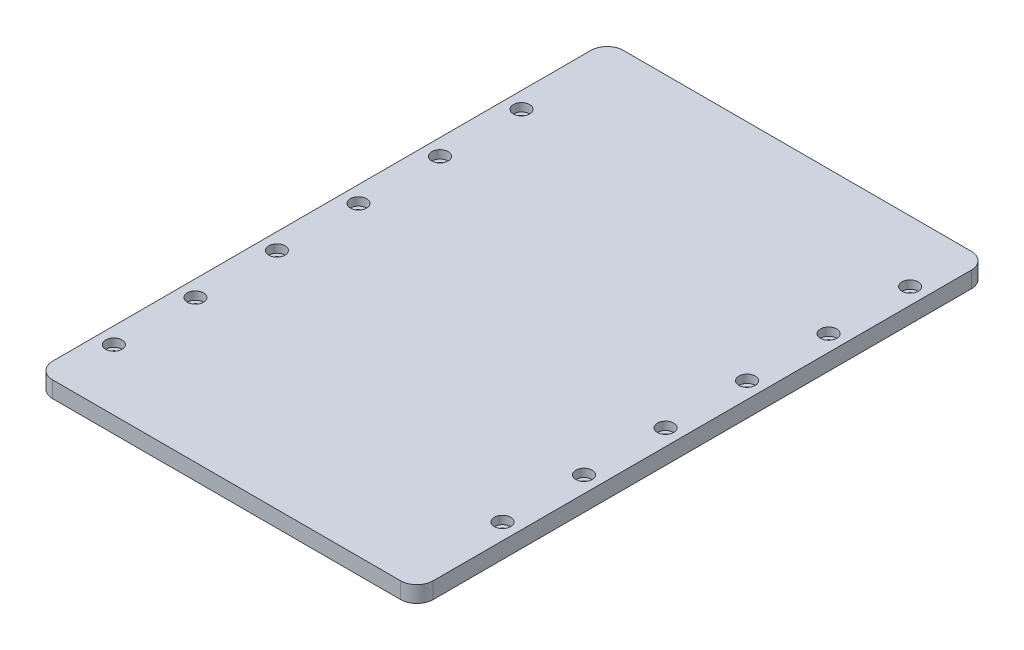
SolidWorks part; units mm, degrees
material "Nylon 101"
ref_plane "前视基准面" through (0, 0, 0) normal (0, 0, 1) x (1, 0, 0)
ref_plane "上视基准面" through (0, 0, 0) normal (0, 1, 0) x (1, 0, 0)
ref_plane "右视基准面" through (0, 0, 0) normal (1, 0, 0) x (0, 0, -1)
sketch "Sketch1" plane through (0, 0, 0) normal (0, 1, 0) x (1, 0, 0)
  line L0 (70, -99) -> (70, 99)
  line L1 (64, 105) -> (-64, 105)
  line L2 (-70, 99) -> (-70, -99)
  line L3 (-64, -105) -> (64, -105)
  arc A0 (70, 99) -> (64, 105) centre (64, 99) ccw
  arc A1 (-64, 105) -> (-70, 99) centre (-64, 99) ccw
  arc A2 (-70, -99) -> (-64, -105) centre (-64, -99) ccw
  arc A3 (64, -105) -> (70, -99) centre (64, -99) ccw
extrude "Boss-Extrude1" add sketch "Sketch1" along normal blind 6
sketch "Sketch2" plane through (0, 6, 0) normal (0, 1, 0) x (1, 0, 0)
  line L0 (-64, -105) -> (64, -105) construction
  circle A0 centre (-64, -82.5) radius 1.5
  circle A1 centre (-64, -52.5) radius 1.5
  circle A2 centre (-64, -22.5) radius 1.5
  circle A3 centre (-64, 7.5) radius 1.5
  circle A4 centre (-64, 37.5) radius 1.5
  circle A5 centre (-64, 67.5) radius 1.5
  circle A6 centre (64, -67.5) radius 1.5
  circle A7 centre (64, -37.5) radius 1.5
  circle A8 centre (64, -7.5) radius 1.5
  circle A9 centre (64, 22.5) radius 1.5
  circle A10 centre (64, 52.5) radius 1.5
  circle A11 centre (64, 82.5) radius 1.5
  dimension "D1" = 22.5
  dimension "D4" = 6
  dimension "D3" = 15
  dimension "D2" = 6
extrude "Cut-Extrude1" cut sketch "Sketch2" against normal blind 10
sketch "Sketch3" plane through (0, 6, 0) normal (0, 1, 0) x (1, 0, 0)
  circle A0 centre (-64, -82.5) radius 1.5 construction
  circle A1 centre (-64, -82.5) radius 1.5
  circle A2 centre (-64, -82.5) radius 3
  circle A3 centre (-64, -52.5) radius 3
  circle A4 centre (-64, -22.5) radius 3
  circle A5 centre (-64, 7.5) radius 3
  circle A6 centre (-64, 37.5) radius 3
  circle A7 centre (-64, 67.5) radius 3
  circle A8 centre (64, -67.5) radius 1.5 construction
  circle A9 centre (64, -67.5) radius 1.5
  circle A10 centre (64, -37.5) radius 1.5
  circle A11 centre (64, -7.5) radius 1.5
  circle A12 centre (64, 22.5) radius 1.5
  circle A13 centre (64, 52.5) radius 1.5
  circle A14 centre (64, 82.5) radius 1.5
  circle A15 centre (64, -67.5) radius 3
  circle A16 centre (64, -37.5) radius 3
  circle A17 centre (64, -7.5) radius 3
  circle A18 centre (64, 22.5) radius 3
  circle A19 centre (64, 52.5) radius 3
  circle A20 centre (64, 82.5) radius 3
  dimension "D1" = 6
  dimension "D3" = 6
  dimension "D2" = 6
extrude "Cut-Extrude2" cut sketch "Sketch3" against normal blind 3
